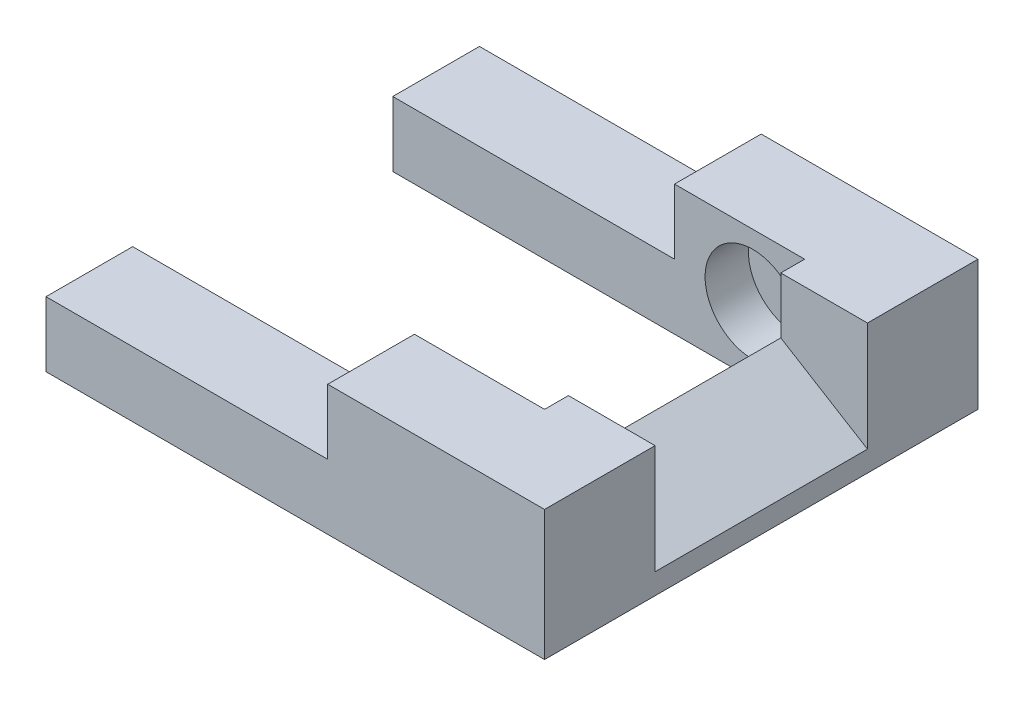
SolidWorks part; units mm, degrees
ref_plane "Ön Düzlem" through (0, 0, 0) normal (0, 0, 1) x (1, 0, 0)
ref_plane "Üst Düzlem" through (0, 0, 0) normal (0, 1, 0) x (1, 0, 0)
ref_plane "Sağ Düzlem" through (0, 0, 0) normal (1, 0, 0) x (0, 0, -1)
sketch "Çizim1" plane through (0, 0, 0) normal (0, 1, 0) x (1, 0, 0)
  line L0 (-20, 80) -> (260, 80)
  line L1 (0, 0) -> (240, 0)
  line L2 (0, 0) -> (0, 60)
  line L3 (0, 60) -> (240, 60)
  line L4 (240, 0) -> (240, 60)
  line L5 (260, -20) -> (260, 80)
  line L6 (-20, -20) -> (260, -20)
  line L7 (-20, -20) -> (-20, 80)
  dimension "D1" = 60
  dimension "D2" = 240
  dimension "D3" = 20
extrude "Yükseklik-Ekstrüzyon1" add sketch "Çizim1" along normal blind 30
sketch "Çizim2" plane through (0, 0, 0) normal (0, -1, 0) x (-1, 0, 0)
  line L0 (0, 0) -> (20, -20) construction
  line L1 (15, -20) -> (15, 9.3947) construction
  line L2 (20, -20) -> (-260, -20) construction
  line L3 (20, -15) -> (0, -15) construction
  line L4 (20, 80) -> (20, -20) construction
  line L5 (-120, -20) -> (-120, 658.3884) construction
  line L6 (-240, 30) -> (0, 30) construction
  line L7 (-240, 0) -> (-240, 60) construction
  line L8 (0, 60) -> (0, 0) construction
  circle A0 centre (10, -10) radius 7.5
  circle A1 centre (-250, -10) radius 7.5
  circle A2 centre (10, 70) radius 7.5
  circle A3 centre (-250, 70) radius 7.5
  circle A4 centre (-120, -10) radius 7.5
  circle A5 centre (-120, 70) radius 7.5
  dimension "D1" = 15
  dimension "D2" = 15
  dimension "D3" = 15
sketch "Çizim3" plane through (0, 0, 20) normal (0, 0, 1) x (1, 0, 0)
  line L0 (-20, 15) -> (37.6853, 15) construction
  line L1 (-20, 30) -> (-20, 0) construction
  line L2 (120, 30) -> (120, -4.2908) construction
  line L3 (-20, 30) -> (260, 30) construction
  circle A0 centre (16.5795, 15) radius 11
  circle A1 centre (228.0369, 15) radius 11
  circle A2 centre (95.4699, 15) radius 11
  dimension "D1" = 22
ref_plane "Düzlem1" through (0, 0, -30) normal (0, 0, 1) x (1, 0, 0)
sketch "Çizim4" plane through (0, 0, -30) normal (0, 0, 1) x (1, 0, 0)
  circle A0 centre (228.0369, 15) radius 11
  circle A1 centre (16.5795, 15) radius 11
  circle A2 centre (95.4699, 15) radius 11
extrude "Kes-Ekstrüzyon1" cut sketch "Çizim4" against normal mid plane 80
sketch "Çizim5" plane through (0, 0, 20) normal (0, 0, 1) x (1, 0, 0)
  line L0 (144.9782, 30) -> (144.9782, 15)
  line L1 (-20, 30) -> (260, 30) construction
  line L2 (-20, 15) -> (37.6853, 15) construction
  line L3 (144.9782, 15) -> (209.9782, 15)
  line L4 (209.9782, 15) -> (209.9782, 30)
  line L6 (144.9782, 30) -> (209.9782, 30)
  dimension "D1" = 65
extrude "Kes-Ekstrüzyon2" cut sketch "Çizim5" against normal blind 119 contours L3 L4 L6 L0
sketch "Çizim6" plane through (0, 0, -30) normal (0, 0, 1) x (1, 0, 0)
  line L0 (234.3599, 20.4676) -> (260, 4.8011)
  line L1 (260, 4.8011) -> (234.3599, 20.4676)
  line L2 (260, 4.8011) -> (260, 31.5523)
  line L3 (260, 31.5523) -> (234.1332, 31.5523)
  line L4 (234.1332, 31.5523) -> (234.3599, 20.4676)
  line L5 (260, 30) -> (260, 0) construction
extrude "Kes-Ekstrüzyon3" cut sketch "Çizim6" against normal mid plane 49 contours L3 L4 L0 L2
sketch "Çizim7" plane through (0, 0, -30) normal (0, 0, 1) x (1, 0, 0)
  circle A0 centre (228.0369, 15) radius 4
  circle A1 centre (95.4699, 15) radius 4
  dimension "D1" = 8
  dimension "D2" = 8
ref_plane "Düzlem2" through (0, 22, 0) normal (0, 1, 0) x (1, 0, 0)
sketch "Çizim10" plane through (0, 22, 0) normal (0, 1, 0) x (1, 0, 0)
  line L0 (55.057, 60) -> (144.9782, 21.1759)
  line L1 (144.9782, 60) -> (0, 60) construction
  line L3 (144.9782, 21.1759) -> (144.9782, 60)
  line L4 (144.9782, 60) -> (55.057, 60)
  line L5 (0, 0) -> (144.9782, 0) construction
  dimension "D1" = 21.1759
extrude "Yükseklik-Ekstrüzyon4" add sketch "Çizim10" along normal blind 8 and the other way blind 1
sketch "Çizim13" plane through (0, 0, -80) normal (0, 0, -1) x (-1, 0, 0)
  circle A0 centre (-16.5795, 15) radius 7.75
  dimension "D1" = 15.5
extrude "Kes-Ekstrüzyon4" cut sketch "Çizim13" against normal blind 18
sketch "Çizim14" plane through (0, 30, 0) normal (0, 1, 0) x (1, 0, 0)
  line L1 (-25.3776, 84.6413) -> (144.9782, 84.6413)
  line L2 (-25.3776, 84.6413) -> (-25.3776, -20)
  line L3 (-25.3776, -20) -> (144.9782, -20)
  line L4 (144.9782, 84.6413) -> (144.9782, -20)
extrude "Kes-Ekstrüzyon6" cut sketch "Çizim14" against normal blind 136
